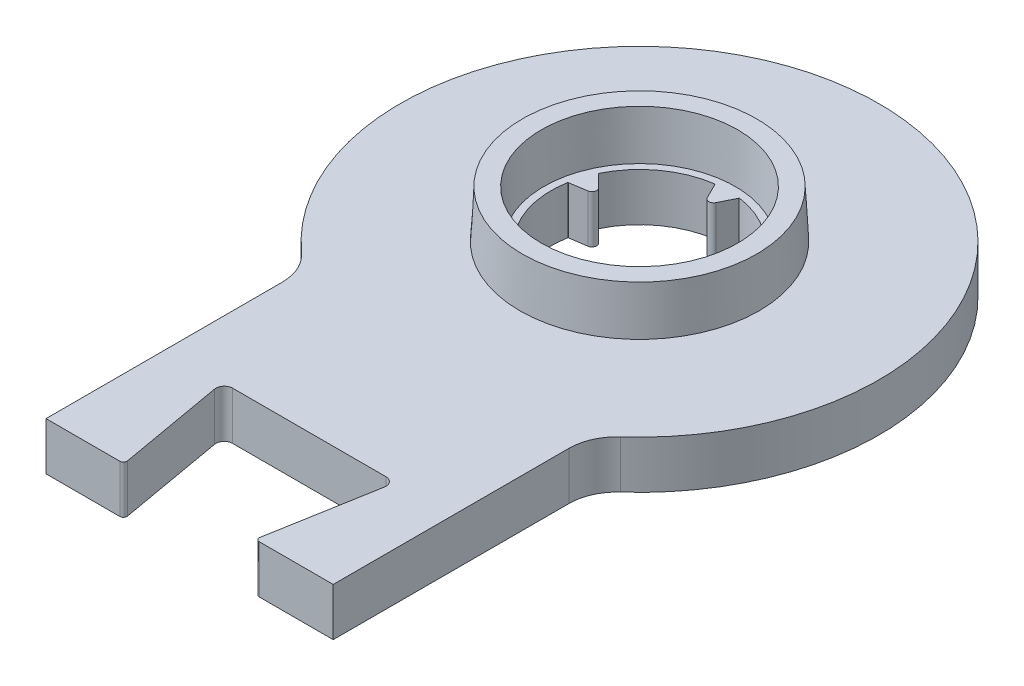
SolidWorks part; units mm, degrees
ref_plane "Front Plane" through (0, 0, 0) normal (0, 0, 1) x (1, 0, 0)
ref_plane "Top Plane" through (0, 0, 0) normal (0, 1, 0) x (1, 0, 0)
ref_plane "Right Plane" through (0, 0, 0) normal (1, 0, 0) x (0, 0, -1)
sketch "Sketch1" plane through (0, 0, 0) normal (0, 1, 0) x (1, 0, 0)
  line L0 (-6, 6) -> (-6, -13.2915)
  line L1 (-6, -19) -> (-2.7023, -19)
  line L2 (6, -19) -> (6, -13.2915)
  line L3 (6, 6) -> (-6, 6)
  line L4 (-6, -13.2915) -> (-6, -19)
  line L5 (6, -13.2915) -> (6, 6)
  line L6 (0, -19) -> (0, 0) construction
  line L7 (-2.6007, -19) -> (-3.5, -13.9) construction
  line L8 (-3.5, -13.9) -> (0, -13.9) construction
  line L9 (-2.7023, -19) -> (-3.6192, -13.8)
  line L10 (-3.6192, -13.8) -> (0, -13.8)
  line L11 (-2.6992, -19.0174) -> (-3.6192, -13.8) construction
  line L12 (2.7023, -19) -> (6, -19)
  line L13 (3.6192, -13.8) -> (0, -13.8)
  line L14 (2.7023, -19) -> (3.6192, -13.8)
  circle A0 centre (0, 0) radius 3.7
  dimension "D1" = 7.4
  dimension "D5" = 6
  dimension "D7" = 80
  dimension "D2" = 25
  dimension "D3" = 6
  dimension "D4" = 12
  dimension "D8" = 3.5
  dimension "D9" = 5.1
  dimension "D10" = 0.1
extrude "Boss-Extrude1" add sketch "Sketch1" along normal blind 2
sketch "Sketch2" plane through (0, 0, 0) normal (0, 1, 0) x (1, 0, 0)
  circle A0 centre (0, 0) radius 10
  circle A1 centre (0, 0) radius 3.8
  dimension "D1" = 20
  dimension "D2" = 7.6
extrude "Boss-Extrude2" add sketch "Sketch2" along normal blind 2
sketch "Sketch3" plane through (0, 0, 0) normal (0, -1, 0) x (1, 0, 0)
  line L0 (-3, 0) -> (-3, 4)
  line L1 (3, 0) -> (3, 4)
  arc A0 (-3, 0) -> (3, 0) centre (0, 0) ccw
  arc A1 (-3, 4) -> (3, 4) centre (0, 0) ccw
extrude "Boss-Extrude3" [suppressed] add sketch "Sketch3" along normal blind 4
fillet "Fillet1" [suppressed] radius 0.5
fillet "Fillet2" [suppressed] radius 1
sketch "Sketch4" plane through (0, 2, 0) normal (0, 1, 0) x (1, 0, 0)
  line L0 (-6, -8) -> (-6, -19) construction
  line L1 (-6, -18.8) -> (6, -18.8)
  line L2 (-6, -18.8) -> (-6, -19)
  line L3 (-6, -19) -> (6, -19)
  line L4 (6, -18.8) -> (6, -19)
  dimension "D1" = 0.2
extrude "Cut-Extrude1" cut sketch "Sketch4" against normal blind 4
fillet "Fillet3" radius 0.35 2 edges at (3.6192, 1, 13.8) (-3.6192, 1, 13.8)
fillet "Fillet4" radius 0.15 2 edges at (2.7375, 1, 18.8) (-2.7375, 1, 18.8)
sketch "Sketch5" plane through (0, 0, 0) normal (0, 1, 0) x (1, 0, 0)
  circle A1 centre (0, 0) radius 3
  circle A2 centre (0, 0) radius 2.1
  dimension "D1" = 4.2
  dimension "D2" = 6
extrude "Boss-Extrude4" [suppressed] add sketch "Sketch5" along normal blind 13
fillet "Fillet5" [suppressed] radius 2
fillet "Fillet6" radius 2 2 edges at (-6, 1, 8) (6, 1, 8)
sketch "Sketch6" plane through (0, 2, 0) normal (0, 1, 0) x (1, 0, 0)
  circle A0 centre (0, 0) radius 3.5
  dimension "D1" = 7
extrude "Boss-Extrude5" [suppressed] add sketch "Sketch6" along normal blind 2 contours A0
sketch "Sketch7" [suppressed] plane through (0, 4, 0) normal (0, 1, 0) x (1, 0, 0)
  circle A0 centre (0, 0) radius 3.15
extrude "Cut-Extrude3" [suppressed] cut sketch "Sketch7" against normal blind 3.2
fillet "Fillet7" [suppressed] radius 2
fillet "Fillet8" [suppressed] radius 1
fillet "Fillet9" [suppressed] radius 0.1
sketch "Sketch8" plane through (0, 2, 0) normal (0, 1, 0) x (1, 0, 0)
  line L0 (0, 0) -> (0, 3.9) construction
  line L1 (-0.5, 3.65) -> (0, 2.65)
  line L2 (-0.5, 4.15) -> (0.5, 4.15)
  line L3 (-0.5, 4.15) -> (-0.5, 3.65)
  line L4 (-0.5, 3.65) -> (0.5, 3.65) construction
  line L5 (0.5, 4.15) -> (0.5, 3.65)
  line L6 (-0.5, 4.15) -> (0.5, 3.65) construction
  line L7 (-0.5, 3.65) -> (0.5, 4.15) construction
  line L8 (0, 2.65) -> (0.5, 3.65)
  dimension "D1" = 3.9
  dimension "D2" = 0.5
  dimension "D3" = 1
  dimension "D4" = 1
extrude "Boss-Extrude6" add sketch "Sketch8" against normal blind 2
pattern_circular "CirPattern1" count 5 over 360 about axis through (0, 0, 0) along (0, 1, 0) of "Boss-Extrude6"
sketch "Sketch11" plane through (0, 2, 0) normal (0, 1, 0) x (1, 0, 0)
  circle A0 centre (0, 0) radius 4
  circle A1 centre (0, 0) radius 5
  dimension "D1" = 8
  dimension "D2" = 10
extrude "Boss-Extrude7" add sketch "Sketch11" along normal blind 2 draft 3
fillet "Fillet10" radius 0.2 5 edges at (1.5576, 1, 2.1439) (2.5203, 1, -0.8189) (0, 1, -2.65) (-2.5203, 1, -0.8189) (-1.5576, 1, 2.1439)
